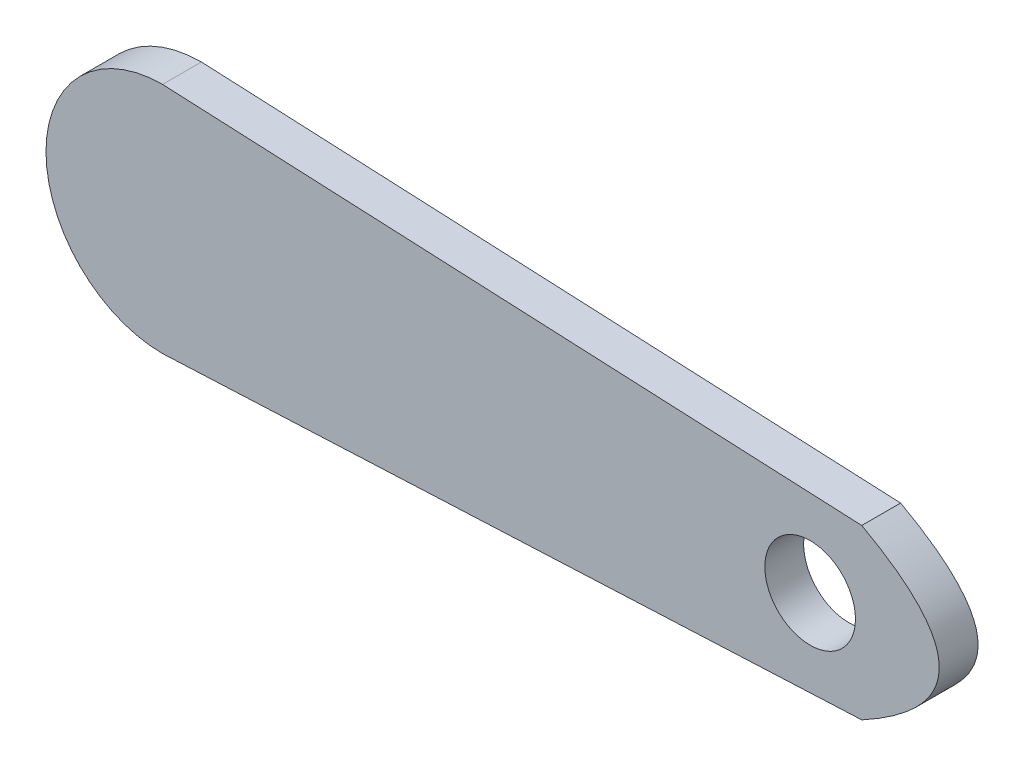
SolidWorks part; units mm, degrees
ref_plane "Front Plane" through (0, 0, 0) normal (0, 0, 1) x (1, 0, 0)
ref_plane "Top Plane" through (0, 0, 0) normal (0, 1, 0) x (1, 0, 0)
ref_plane "Right Plane" through (0, 0, 0) normal (1, 0, 0) x (0, 0, -1)
sketch "Sketch1" plane through (0, 0, 0) normal (0, 0, 1) x (1, 0, 0)
  line L0 (-25, 0) -> (25, 0)
  line L1 (25, -16.878) -> (25, 16.878) construction
  line L2 (-25, -9) -> (-25, 9)
  line L3 (25, 0) -> (28.9855, 0) construction
  line L4 (28.9855, -6.5) -> (28.9855, 6.5)
  line L5 (-25, 9) -> (28.9855, 6.5)
  line L6 (-25, -9) -> (28.9855, -6.5)
  circle A0 centre (25, 0) radius 3.5
  arc A1 (-25, 9) -> (-25, -9) centre (-25, 0) ccw
  spline S0 degree 2 poles (28.9855, 6.5) (40.9467, 0) (28.9855, -6.5) knots 0 0 0 1 1 1
  point P4 (0, 0)
  point P8 (25, 0)
  point P14 (28.9855, 0)
  point P15 (0, 0)
  point P16 (34.9661, 0)
  dimension "D2" = 7
  dimension "D3" = 18
  dimension "D1" = 50
  dimension "D4" = 3.9855
  dimension "D5" = 13
extrude "Boss-Extrude1" add sketch "Sketch1" along normal blind 3
